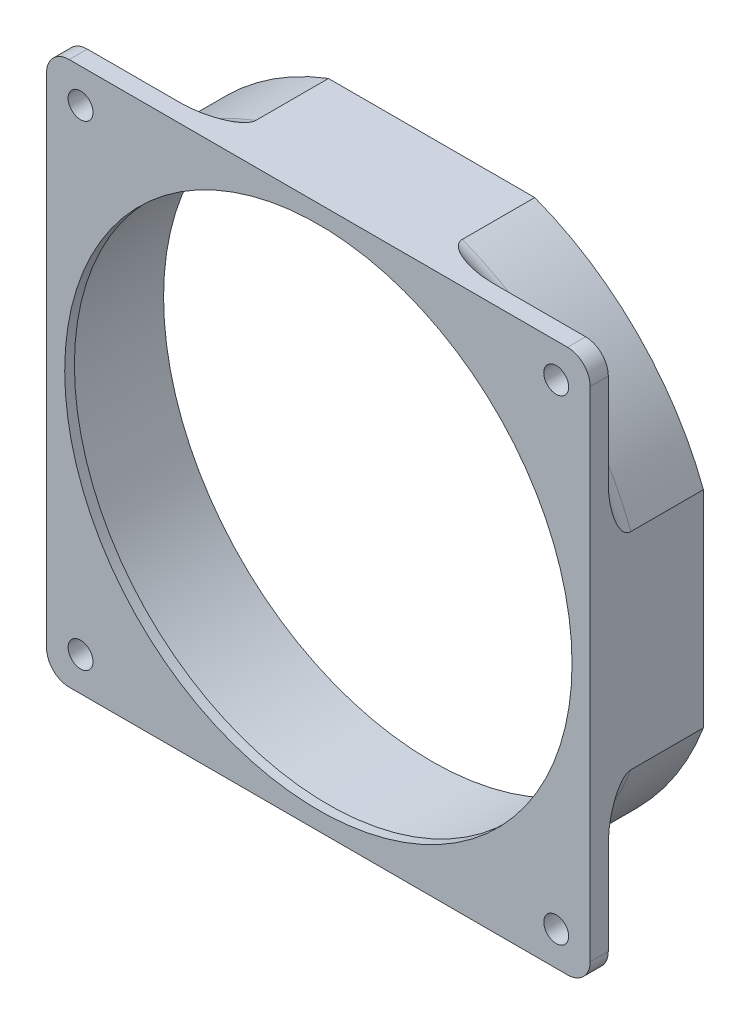
SolidWorks part; units mm, degrees
ref_plane "Front Plane" through (0, 0, 0) normal (0, 0, 1) x (1, 0, 0)
ref_plane "Top Plane" through (0, 0, 0) normal (0, 1, 0) x (1, 0, 0)
ref_plane "Right Plane" through (0, 0, 0) normal (1, 0, 0) x (0, 0, -1)
sketch "Sketch1" plane through (0, 0, 0) normal (0, 0, 1) x (1, 0, 0)
  line L1 (-55, -60) -> (55, -60)
  line L2 (-60, -55) -> (-60, 55)
  line L3 (-55, 60) -> (55, 60)
  line L4 (60, -55) -> (60, 55)
  line L5 (-60, -60) -> (60, 60) construction
  line L6 (-60, 60) -> (60, -60) construction
  circle A0 centre (0, 0) radius 56
  circle A1 centre (-52.5, 52.5) radius 2.75
  circle A2 centre (52.5, 52.5) radius 2.75
  circle A3 centre (52.5, -52.5) radius 2.75
  circle A4 centre (-52.5, -52.5) radius 2.75
  arc A5 (-55, -60) -> (-60, -55) centre (-55, -55) cw
  arc A6 (55, -60) -> (60, -55) centre (55, -55) ccw
  arc A7 (55, 60) -> (60, 55) centre (55, 55) cw
  arc A8 (-60, 55) -> (-55, 60) centre (-55, 55) cw
  point P18 (0, 0)
  dimension "D1" = 112
  dimension "D3" = 5.5
  dimension "D6" = 5
  dimension "D2" = 120
  dimension "D5" = 105
  dimension "D4" = 4
extrude "Boss-Extrude1" add sketch "Sketch1" along normal mid plane 25
sketch "Sketch2" plane through (0, 0, -12.5) normal (0, 0, -1) x (-1, 0, 0)
  circle A0 centre (0, 0) radius 56 construction
  circle A1 centre (0, 0) radius 56
  circle A2 centre (0, 0) radius 59.175
  dimension "D1" = 3.175
extrude "Cut-Extrude1" cut sketch "Sketch2" against normal blind 22.86
sketch "Sketch3" plane through (0, 0, -12.5) normal (0, 0, -1) x (-1, 0, 0)
  line L0 (-60, -22.7691) -> (-60, -55)
  line L1 (-22.7691, 60) -> (-55, 60)
  line L2 (60, 22.7691) -> (60, 55)
  line L3 (22.7691, -60) -> (55, -60)
  line L4 (60, -55) -> (60, 55)
  line L5 (55, 60) -> (-55, 60)
  line L6 (-60, 55) -> (-60, -55)
  line L7 (-55, -60) -> (55, -60)
  line L8 (60, -55) -> (60, -22.7691)
  line L9 (55, 60) -> (22.7691, 60)
  line L10 (-60, 55) -> (-60, 22.7691)
  line L11 (-55, -60) -> (-22.7691, -60)
  arc A1 (-22.7691, 60) -> (-60, 22.7691) centre (0, 0) ccw
  circle A2 centre (0, 0) radius 64.175
  arc A3 (-60, -22.7691) -> (-22.7691, -60) centre (0, 0) ccw
  arc A4 (60, 22.7691) -> (22.7691, 60) centre (0, 0) ccw
  arc A5 (22.7691, -60) -> (60, -22.7691) centre (0, 0) ccw
  arc A7 (55, -60) -> (60, -55) centre (55, -55) ccw
  arc A8 (60, 55) -> (55, 60) centre (55, 55) ccw
  arc A9 (-55, 60) -> (-60, 55) centre (-55, 55) ccw
  arc A10 (-60, -55) -> (-55, -60) centre (-55, -55) ccw
  arc A11 (55, -60) -> (60, -55) centre (55, -55) ccw
  arc A12 (60, 55) -> (55, 60) centre (55, 55) ccw
  arc A13 (-55, 60) -> (-60, 55) centre (-55, 55) ccw
  arc A14 (-60, -55) -> (-55, -60) centre (-55, -55) ccw
  dimension "D1" = 5
  dimension "D2" = 0
extrude "Cut-Extrude2" cut sketch "Sketch3" against normal offset from surface (21 mm away) 4 up to face at (0, 0, 12.5)
fillet "Fillet1" radius 5 4 edges at (45.3786, 45.3786, 8.5) (-45.3786, 45.3786, 8.5) (-45.3786, -45.3786, 8.5) (45.3786, -45.3786, 8.5)
